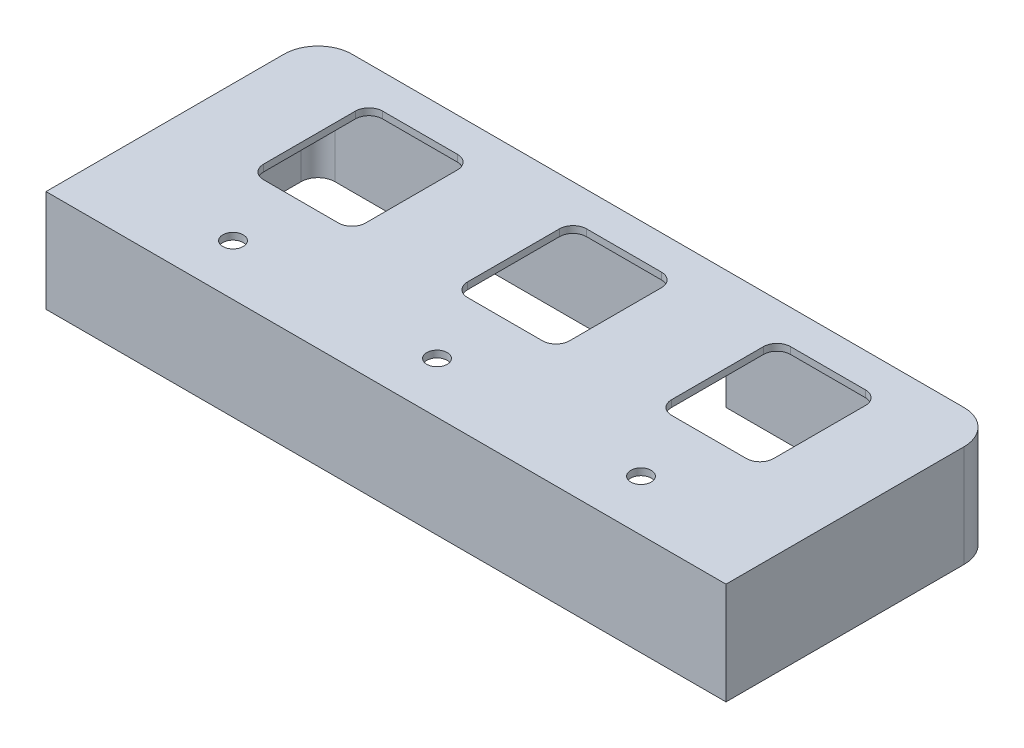
SolidWorks part; units mm, degrees
material "Калифорния"
ref_plane "Спереди" through (0, 0, 0) normal (0, 0, 1) x (1, 0, 0)
ref_plane "Сверху" through (0, 0, 0) normal (0, 1, 0) x (1, 0, 0)
ref_plane "Справа" through (0, 0, 0) normal (1, 0, 0) x (0, 0, -1)
sketch "Эскиз лицевой стороны" plane through (0, 0, 0) normal (0, 1, 0) x (1, 0, 0)
  line L0 (49, 30) -> (71, 30)
  line L1 (-90, 40) -> (90, 40)
  line L2 (-100, 30) -> (-100, -40)
  line L3 (-100, -40) -> (100, -40)
  line L4 (100, 30) -> (100, -40)
  line L5 (45, 26) -> (45, -1)
  line L6 (49, -5) -> (71, -5)
  line L7 (75, 26) -> (75, -1)
  line L8 (-11, 30) -> (11, 30)
  line L9 (-15, 26) -> (-15, -1)
  line L10 (-11, -5) -> (11, -5)
  line L11 (15, 26) -> (15, -1)
  line L12 (-71, 30) -> (-49, 30)
  line L13 (-75, 26) -> (-75, -1)
  line L14 (-71, -5) -> (-49, -5)
  line L15 (-45, 26) -> (-45, -1)
  line L16 (49, 30) -> (-11, 30) construction
  arc A2 (90, 40) -> (100, 30) centre (90, 30) cw
  arc A3 (-90, 40) -> (-100, 30) centre (-90, 30) ccw
  arc A4 (45, -1) -> (49, -5) centre (49, -1) ccw
  arc A5 (71, -5) -> (75, -1) centre (71, -1) ccw
  arc A6 (71, 30) -> (75, 26) centre (71, 26) cw
  arc A7 (49, 30) -> (45, 26) centre (49, 26) ccw
  arc A8 (-15, -1) -> (-11, -5) centre (-11, -1) ccw
  arc A9 (11, -5) -> (15, -1) centre (11, -1) ccw
  arc A10 (11, 30) -> (15, 26) centre (11, 26) cw
  arc A11 (-11, 30) -> (-15, 26) centre (-11, 26) ccw
  arc A12 (-75, -1) -> (-71, -5) centre (-71, -1) ccw
  arc A13 (-49, -5) -> (-45, -1) centre (-49, -1) ccw
  arc A14 (-49, 30) -> (-45, 26) centre (-49, 26) cw
  arc A15 (-71, 30) -> (-75, 26) centre (-71, 26) ccw
  circle A16 centre (60, -25) radius 3
  circle A17 centre (0, -25) radius 3
  circle A18 centre (-60, -25) radius 3
  point P8 (-100, -40)
  point P13 (100, 40)
  point P16 (-100, 40)
  dimension "D6" = 4
  dimension "D13" = 6
  dimension "D5" = 10
  dimension "D1" = 200
  dimension "D2" = 80
  dimension "D3" = 100
  dimension "D4" = 40
  dimension "D7" = 30
  dimension "D8" = 35
  dimension "D10" = 10
  dimension "D9" = 45
  dimension "D12" = 60
  dimension "D14" = 15
  dimension "D15" = 20
  dimension "D11" = 3
extrude "Лицевая сторона" add sketch "Эскиз лицевой стороны" against normal blind 2
sketch "Эскиз стенок" plane through (0, 0, 0) normal (0, 1, 0) x (1, 0, 0)
  line L0 (-90, 40) -> (90, 40)
  line L1 (-100, 30) -> (-100, -40)
  line L2 (-100, -40) -> (100, -40)
  line L3 (100, 30) -> (100, -40)
  line L13 (-90, 35) -> (90, 35)
  line L14 (95, 30) -> (95, -35)
  line L15 (-95, -35) -> (95, -35)
  line L16 (-95, 30) -> (-95, -35)
  arc A8 (100, 30) -> (90, 40) centre (90, 30) ccw
  arc A9 (-100, 30) -> (-90, 40) centre (-90, 30) cw
  arc A12 (95, 30) -> (90, 35) centre (90, 30) ccw
  arc A13 (-95, 30) -> (-90, 35) centre (-90, 30) cw
  dimension "D1" = 10
  dimension "D2" = 200
  dimension "D3" = 80
  dimension "D4" = 100
  dimension "D5" = 40
  dimension "D6" = 5
extrude "Стенки" add sketch "Эскиз стенок" against normal blind 30
ref_plane "Плоскость кабель-канала" through (0, -30, 0) normal (0, 1, 0) x (1, 0, 0)
sketch "Эскиз кабель-канала" plane through (0, -30, 0) normal (0, 1, 0) x (1, 0, 0)
  line L0 (90, 40) -> (-90, 40) construction
  line L1 (-5, 40) -> (25, 40)
  line L2 (-5, 40) -> (-5, 35)
  line L3 (-5, 35) -> (25, 35)
  line L4 (25, 40) -> (25, 35)
  line L5 (90, 35) -> (-90, 35) construction
  dimension "D1" = 30
  dimension "D2" = 5
extrude "Кабель-канал" cut sketch "Эскиз кабель-канала" along normal blind 10
equation "\"width\"= 200мм"
equation "\"height\"= 80мм"
equation "\"D1@Эскиз лицевой стороны\"=\"width\""
equation "\"D2@Эскиз лицевой стороны\"=\"height\""
equation "\"D4@Эскиз лицевой стороны\"=\"height\"/2"
equation "\"D3@Эскиз лицевой стороны\"=\"width\"/2"
equation "\"D2@Эскиз стенок\"=\"width\""
equation "\"D3@Эскиз стенок\"=\"height\""
equation "\"external_radius\"= 10.00мм"
equation "\"D1@Эскиз стенок\"=\"external_radius\""
equation "\"D5@Эскиз лицевой стороны\"=\"external_radius\""
